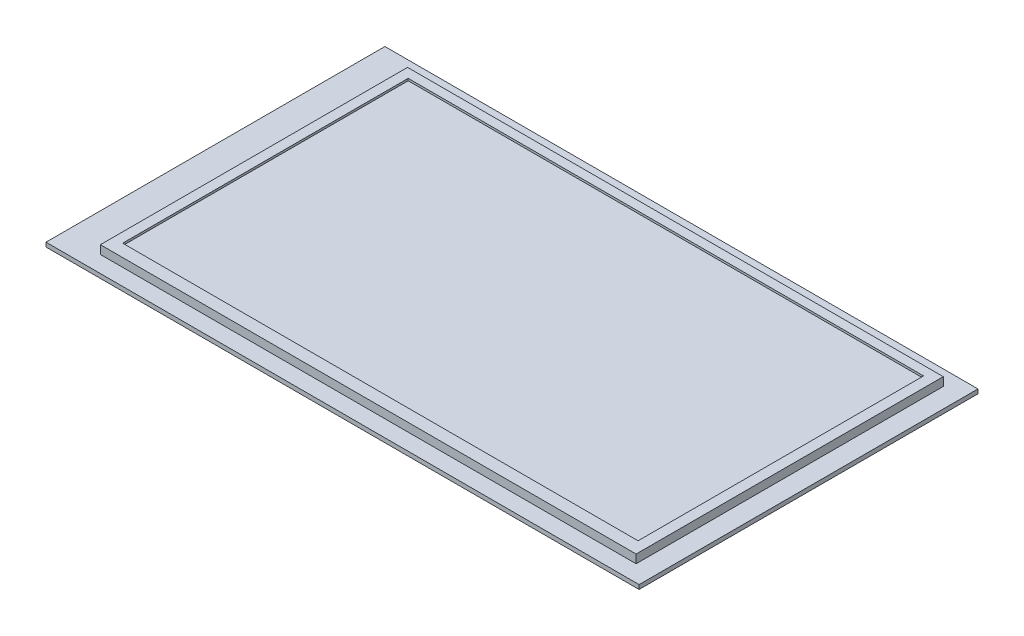
SolidWorks part; units mm, degrees
ref_plane "前视基准面" through (0, 0, 0) normal (0, 0, 1) x (1, 0, 0)
ref_plane "上视基准面" through (0, 0, 0) normal (0, 1, 0) x (1, 0, 0)
ref_plane "右视基准面" through (0, 0, 0) normal (1, 0, 0) x (0, 0, -1)
sketch "草图1" plane through (0, 0, 0) normal (0, 1, 0) x (1, 0, 0)
  line L1 (0, 0) -> (140, 0)
  line L2 (0, 0) -> (0, -80)
  line L3 (0, -80) -> (140, -80)
  line L4 (140, 0) -> (140, -80)
  dimension "D1" = 140
  dimension "D2" = 80
extrude "凸台-拉伸1" add sketch "草图1" along normal blind 1
sketch "草图2" plane through (0, 1, 0) normal (0, 1, 0) x (1, 0, 0)
  line L1 (8.935, -3.5929) -> (135.3936, -3.5929)
  line L2 (8.935, -3.5929) -> (8.935, -76.0979)
  line L3 (8.935, -76.0979) -> (135.3936, -76.0979)
  line L4 (135.3936, -3.5929) -> (135.3936, -76.0979)
extrude "凸台-拉伸2" add sketch "草图2" along normal blind 2
sketch "草图3" plane through (0, 3, 0) normal (0, 1, 0) x (1, 0, 0)
  line L1 (11.2539, -5.7572) -> (132.9201, -5.7572)
  line L2 (11.2539, -5.7572) -> (11.2539, -73.1606)
  line L3 (11.2539, -73.1606) -> (132.9201, -73.1606)
  line L4 (132.9201, -5.7572) -> (132.9201, -73.1606)
extrude "切除-拉伸1" cut sketch "草图3" against normal blind 0.5 contours L2 L1 L4 L3
